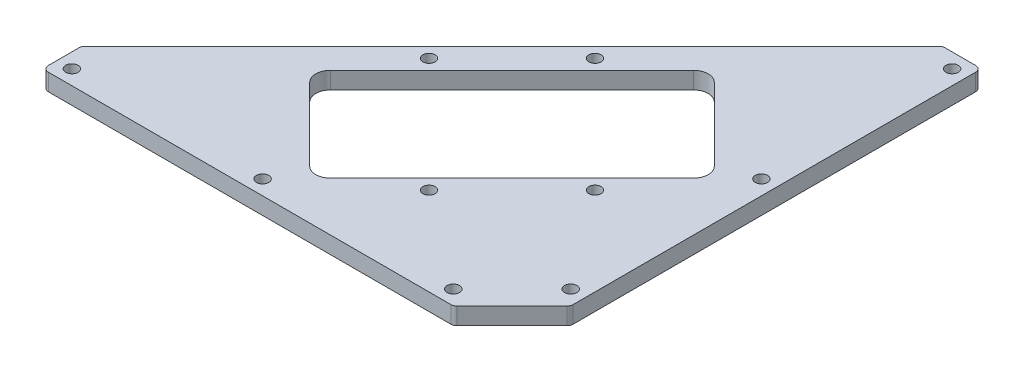
SolidWorks part; units mm, degrees
material "MC901"
ref_plane "正面" through (0, 0, 0) normal (0, 0, 1) x (1, 0, 0)
ref_plane "平面" through (0, 0, 0) normal (0, 1, 0) x (1, 0, 0)
ref_plane "右側面" through (0, 0, 0) normal (1, 0, 0) x (0, 0, -1)
sketch "ｽｹｯﾁ1" plane through (0, 0, 0) normal (0, 1, 0) x (1, 0, 0)
  line L0 (0, 20) -> (0, 160)
  line L1 (0, 175) -> (-5, 170) construction
  line L2 (-160, 0) -> (-20, 0)
  line L3 (-5, 0) -> (-5, 76.3173) construction
  line L4 (0, 0) -> (-87.5, 87.5) construction
  line L5 (-20, 0) -> (0, 20)
  line L6 (-82.2012, 13.2583) -> (-13.2583, 82.2012)
  line L7 (-97.2272, 68.9429) -> (-58.3363, 30.052) construction
  line L8 (-97.2272, 68.9429) -> (-68.9429, 97.2272) construction
  line L9 (-58.3363, 30.052) -> (-30.052, 58.3363) construction
  line L10 (-68.9429, 97.2272) -> (-30.052, 58.3363) construction
  line L11 (-97.2272, 68.9429) -> (-30.052, 58.3363) construction
  line L12 (-58.3363, 30.052) -> (-68.9429, 97.2272) construction
  line L13 (-63.6396, 63.6396) -> (-49.4975, 77.7817) construction
  line L14 (-10, 165) -> (-10, 0) construction
  line L15 (-82.2012, 13.2583) -> (-114.021, 45.0781)
  line L16 (-13.2583, 82.2012) -> (-45.0781, 114.021)
  line L17 (-114.021, 45.0781) -> (-45.0781, 114.021)
  line L18 (-82.2012, 13.2583) -> (-45.0781, 114.021) construction
  line L19 (-13.2583, 82.2012) -> (-114.021, 45.0781) construction
  line L20 (-20, 0) -> (-10, 0) construction
  line L21 (-5, 0) -> (0, 0) construction
  line L22 (-10, 0) -> (-5, 0) construction
  line L23 (0, 0) -> (0, 20) construction
  line L24 (-128.1631, 45.0781) -> (-45.0781, 128.1631)
  line L25 (0.8839, 82.2012) -> (0, 83.085) construction
  line L26 (-82.2012, -0.8839) -> (-81.3173, 0) construction
  line L27 (-128.0456, 44.9606) -> (-128.1631, 45.0781)
  line L30 (-45.0781, 128.1631) -> (-13.2412, 160)
  line L32 (0.8839, 82.2012) -> (-45.0781, 128.1631) construction
  line L33 (-5, 88.085) -> (-10, 93.085) construction
  line L34 (0, 83.085) -> (-5, 88.085) construction
  line L35 (0, 81.3173) -> (0.8839, 82.2012) construction
  line L36 (-82.2012, -0.8839) -> (0.8839, 82.2012) construction
  line L37 (-10, 71.3173) -> (-5, 76.3173) construction
  line L38 (-5, 76.3173) -> (0, 81.3173) construction
  line L39 (-5, 76.3173) -> (-5, 88.085) construction
  line L40 (-5, 88.085) -> (-5, 170) construction
  line L41 (-40.6586, 40.6586) -> (-10, 71.3173) construction
  line L42 (-81.3173, 0) -> (-40.6586, 40.6586) construction
  line L43 (-82.2012, -0.8839) -> (-83.085, 0) construction
  line L44 (-82.2012, -0.8839) -> (-128.1631, 45.0781) construction
  line L45 (-83.085, 0) -> (-128.0456, 44.9606) construction
  line L46 (-175, 0) -> (-160, 0) construction
  line L47 (-87.5, 87.5) -> (-175, 0) construction
  line L48 (-10, 165) -> (-87.5, 87.5) construction
  line L49 (-5, 170) -> (-10, 165) construction
  line L50 (0, 160) -> (0, 175)
  line L51 (0, 160) -> (-10, 160)
  line L52 (-13.2412, 160) -> (-10, 160)
  line L53 (-128.1631, 45.0781) -> (-160, 13.2412)
  line L54 (-160, 13.2412) -> (-160, 10)
  line L55 (-160, 0) -> (-160, 10)
  circle A0 centre (-5, 25) radius 2.1
  circle A1 centre (-5, 90) radius 2.1
  circle A2 centre (-90, 5) radius 2.1
  circle A3 centre (-25, 5) radius 2.1
  circle A4 centre (-68.9429, 97.2272) radius 2.1
  circle A5 centre (-30.052, 58.3363) radius 2.1
  circle A6 centre (-58.3363, 30.052) radius 2.1
  circle A7 centre (-97.2272, 68.9429) radius 2.1
  circle A8 centre (-5, 155) radius 2.1
  circle A9 centre (-155, 5) radius 2.1
  point P20 (-63.6396, 63.6396)
  dimension "D3" = 4.2
  dimension "D9" = 4.2
  dimension "D1" = 5
  dimension "D2" = 170
  dimension "D4" = 25
  dimension "D5" = 65
  dimension "D6" = 65
  dimension "D7" = 40
  dimension "D8" = 55
  dimension "D10" = 10
  dimension "D11" = 90
  dimension "D12" = 20
  dimension "D13" = 45
  dimension "D14" = 97.5
  dimension "D16" = 5
  dimension "D15" = 10
extrude "ﾎﾞｽ - 押し出し1" add sketch "ｽｹｯﾁ1" along normal blind 5.8
sketch "ｽｹｯﾁ2" plane through (0, 5.8, 0) normal (0, 1, 0) x (1, 0, 0)
  line L0 (-86.6206, 86.6206) -> (-10, 10) construction
  line L1 (-160, 13.2412) -> (-13.2412, 160) construction
  line L2 (-20, 0) -> (0, 20) construction
  line L3 (0, 20) -> (0, 160) construction
  line L4 (0, 30) -> (13.8, 30)
  line L5 (0, 30) -> (0, 50)
  line L6 (0, 50) -> (13.8, 50)
  line L7 (15.8, 32) -> (15.8, 48)
  line L8 (15.8, 40) -> (10.8, 40) construction
  line L9 (-160, 0) -> (-20, 0) construction
  line L10 (0, 130) -> (13.8, 130)
  line L11 (0, 130) -> (0, 150)
  line L12 (0, 150) -> (13.8, 150)
  line L13 (15.8, 132) -> (15.8, 148)
  line L14 (15.8, 140) -> (10.8, 140) construction
  line L15 (0, 30) -> (0, 130) construction
  line L16 (-30, 0) -> (-130, 0) construction
  line L17 (-140, -15.8) -> (-140, -10.8) construction
  line L18 (-40, -15.8) -> (-40, -10.8) construction
  line L19 (-132, -15.8) -> (-148, -15.8)
  line L20 (-150, 0) -> (-150, -13.8)
  line L21 (-130, 0) -> (-150, 0)
  line L22 (-130, 0) -> (-130, -13.8)
  line L23 (-32, -15.8) -> (-48, -15.8)
  line L24 (-50, 0) -> (-50, -13.8)
  line L25 (-30, 0) -> (-50, 0)
  line L26 (-30, 0) -> (-30, -13.8)
  circle A0 centre (10.8, 40) radius 1.6
  arc A1 (13.8, 30) -> (15.8, 32) centre (13.8, 32) ccw
  arc A2 (13.8, 50) -> (15.8, 48) centre (13.8, 48) cw
  circle A3 centre (10.8, 140) radius 1.6
  arc A4 (13.8, 130) -> (15.8, 132) centre (13.8, 132) ccw
  arc A5 (13.8, 150) -> (15.8, 148) centre (13.8, 148) cw
  arc A6 (-150, -13.8) -> (-148, -15.8) centre (-148, -13.8) ccw
  arc A7 (-130, -13.8) -> (-132, -15.8) centre (-132, -13.8) cw
  circle A8 centre (-140, -10.8) radius 1.6
  arc A9 (-50, -13.8) -> (-48, -15.8) centre (-48, -13.8) ccw
  arc A10 (-30, -13.8) -> (-32, -15.8) centre (-32, -13.8) cw
  circle A11 centre (-40, -10.8) radius 1.6
  point P19 (15.8, 30)
  point P22 (15.8, 50)
  point P58 (-50, -15.8)
  point P59 (-30, -15.8)
  dimension "D3" = 3.2
  dimension "D6" = 2
  dimension "D1" = 15.8
  dimension "D2" = 20
  dimension "D4" = 5
  dimension "D5" = 30
  dimension "D8" = 100
  dimension "D7" = 2
extrude "ﾎﾞｽ - 押し出し2" [suppressed] add sketch "ｽｹｯﾁ2" against normal blind 5.8
fillet "ﾌｨﾚｯﾄ1" radius 2 6 edges at (0, 2.9, -20) (-20, 2.9, 0) (-13.2412, 2.9, -160) (0, 2.9, -160) (-160, 2.9, 0) (-160, 2.9, -13.2412)
fillet "ﾌｨﾚｯﾄ2" radius 5 4 edges at (-114.021, 2.9, -45.0781) (-82.2012, 2.9, -13.2583) (-13.2583, 2.9, -82.2012) (-45.0781, 2.9, -114.021)
